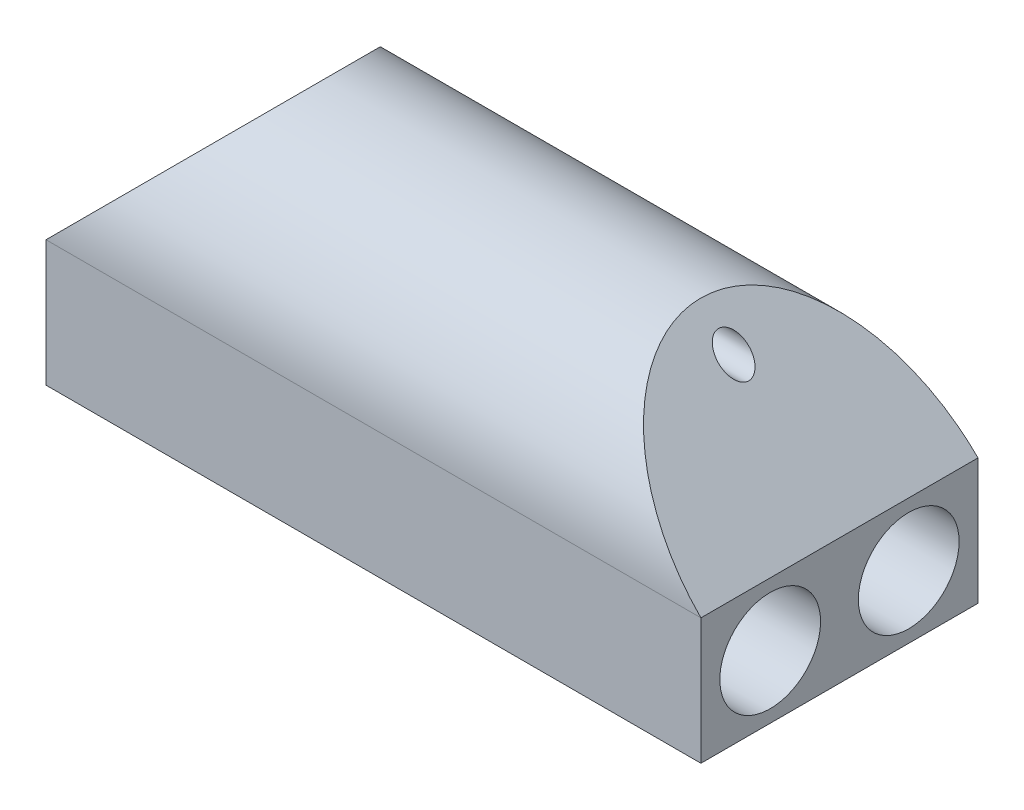
SolidWorks part; units mm, degrees
ref_plane "Front Plane" through (0, 0, 0) normal (0, 0, 1) x (1, 0, 0)
ref_plane "Top Plane" through (0, 0, 0) normal (0, 1, 0) x (1, 0, 0)
ref_plane "Right Plane" through (0, 0, 0) normal (1, 0, 0) x (0, 0, -1)
sketch "Sketch1" plane through (0, 0, 0) normal (0, 1, 0) x (1, 0, 0)
  line L1 (0, 0) -> (-33.02, 0)
  line L2 (0, 0) -> (0, 13.97)
  line L3 (0, 13.97) -> (-33.02, 13.97)
  line L4 (-33.02, 0) -> (-33.02, 13.97)
  dimension "length" = 33.02
  dimension "width" = 13.97
extrude "depth a" add sketch "Sketch1" along normal blind 6.35
sketch "Sketch4" plane through (0, 0, 0) normal (1, 0, 0) x (0, 0, -1)
  line L3 (0, 6.35) -> (13.97, 6.35) construction
  line L4 (0, 6.35) -> (13.97, 6.35)
  arc A0 (0, 6.35) -> (13.97, 6.35) centre (6.985, 6.35) cw
extrude "round extrude" add sketch "Sketch4" against normal up to surface (33.02 mm away) up to face at (-33.02, 3.175, -6.985)
sketch "Sketch5" plane through (0, 0, 0) normal (0, 0, 1) x (1, 0, 0)
  line L0 (0, 6.35) -> (0, 13.335)
  line L1 (0, 13.335) -> (-6.985, 13.335)
  line L2 (0, 13.335) -> (-33.02, 13.335) construction
  line L3 (-6.985, 13.335) -> (0, 6.35)
  line L4 (-16.51, -3.2288) -> (-16.51, 15.9288) construction
  line L6 (-33.02, 6.35) -> (-33.02, 13.335)
  line L7 (-33.02, 13.335) -> (-26.035, 13.335)
  line L8 (-26.035, 13.335) -> (-33.02, 6.35)
  line L9 (-33.02, 6.35) -> (0, 6.35) construction
  point P10 (-16.51, 6.35)
  point P16 (-16.51, 6.35)
  dimension "D1" = 45
extrude "angle cut" cut sketch "Sketch5" against normal through all
sketch "string hole " plane through (0, 0, 0) normal (1, 0, 0) x (0, 0, -1)
  line L0 (6.985, 6.35) -> (6.985, 13.335) construction
  line L1 (13.97, 6.35) -> (0, 6.35) construction
  circle A0 centre (6.985, 11.684) radius 0.762
  arc A1 (13.97, 6.35) -> (0, 6.35) centre (6.985, 6.35) ccw construction
  dimension "D1" = 1.524
  dimension "D2" = 5.334
extrude "string hole cut" cut sketch "string hole " against normal through all
sketch "elastic holes" plane through (0, 0, 0) normal (1, 0, 0) x (0, 0, -1)
  line L1 (13.97, 6.35) -> (0, 6.35) construction
  line L2 (0, 0) -> (13.97, 0) construction
  line L3 (6.985, 0) -> (6.985, 6.35) construction
  line L5 (6.985, 3.175) -> (0, 3.175) construction
  line L7 (0, 6.35) -> (0, 0) construction
  circle A0 centre (3.4925, 3.175) radius 2.54
  circle A1 centre (10.4775, 3.175) radius 2.54
  point P5 (6.985, 6.35)
  point P8 (3.4925, 3.175)
  point P13 (6.985, 3.175)
  point P17 (6.985, 0)
  point P20 (0, 3.175)
  dimension "D1" = 5.08
extrude "elastic hole cut" cut sketch "elastic holes" against normal through all
sketch "guide" plane through (0, 0, 0) normal (0, 1, 0) x (1, 0, 0)
  line L0 (-33.02, 13.97) -> (-33.02, 0) construction
  line L1 (-33.02, 13.97) -> (-33.02, 0)
  arc A0 (-33.02, 13.97) -> (-33.02, 0) centre (-40.398, 6.985) cw
  arc A1 (-33.02, 0) -> (-33.02, 13.97) centre (-33.02, 6.985) ccw construction
  dimension "D1" = 10.16
extrude "guide cut" cut sketch "guide" along normal up to surface (6.35 mm away)
